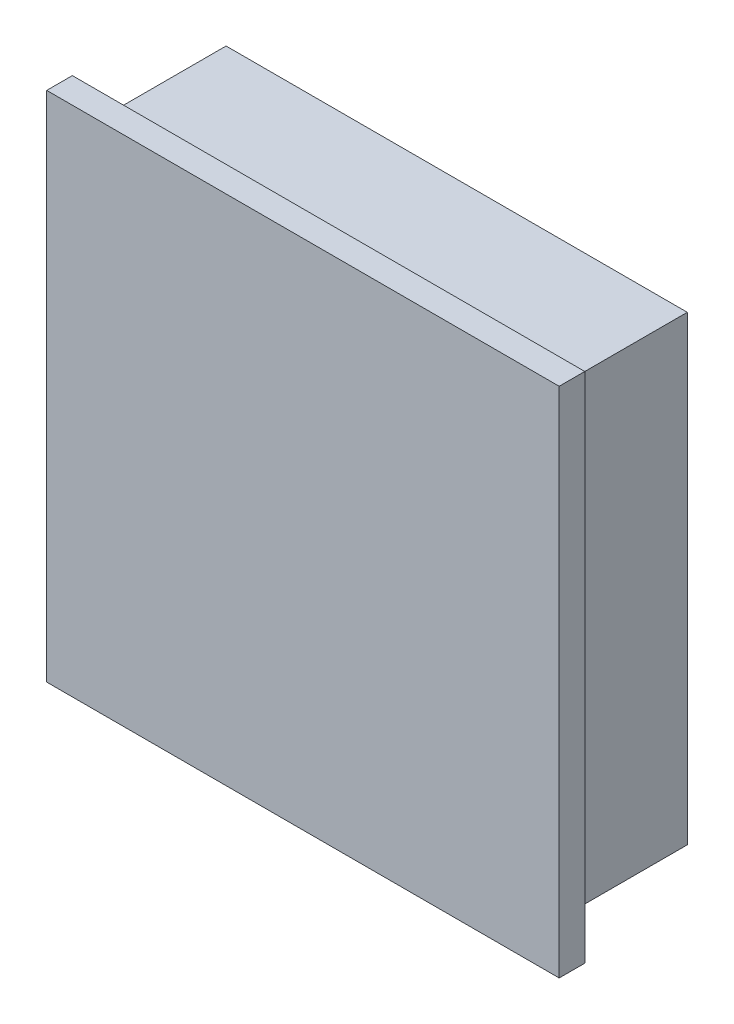
SolidWorks part; units mm, degrees
ref_plane "Front Plane" through (0, 0, 0) normal (0, 0, 1) x (1, 0, 0)
ref_plane "Top Plane" through (0, 0, 0) normal (0, 1, 0) x (1, 0, 0)
ref_plane "Right Plane" through (0, 0, 0) normal (1, 0, 0) x (0, 0, -1)
sketch "Sketch1" plane through (0, 0, 0) normal (0, 0, 1) x (1, 0, 0)
  line L1 (0, 0) -> (36, 0)
  line L2 (0, 0) -> (0, 36)
  line L3 (0, 36) -> (36, 36)
  line L4 (36, 0) -> (36, 36)
  dimension "D1" = 36
extrude "Boss-Extrude1" add sketch "Sketch1" along normal blind 10
sketch "Sketch2" plane through (0, 0, 10) normal (0, 0, 1) x (1, 0, 0)
  line L0 (0, 36) -> (0, 0) construction
  line L1 (-2, 38) -> (38, 38)
  line L2 (-2, 38) -> (-2, -2)
  line L3 (-2, -2) -> (38, -2)
  line L4 (38, 38) -> (38, -2)
  line L5 (36, 0) -> (36, 36) construction
  line L6 (36, 36) -> (0, 36) construction
  line L7 (0, 0) -> (36, 0) construction
  dimension "D1" = 2
  dimension "D2" = 2
  dimension "D3" = 2
  dimension "D4" = 2
extrude "Boss-Extrude2" add sketch "Sketch2" along normal blind 2
